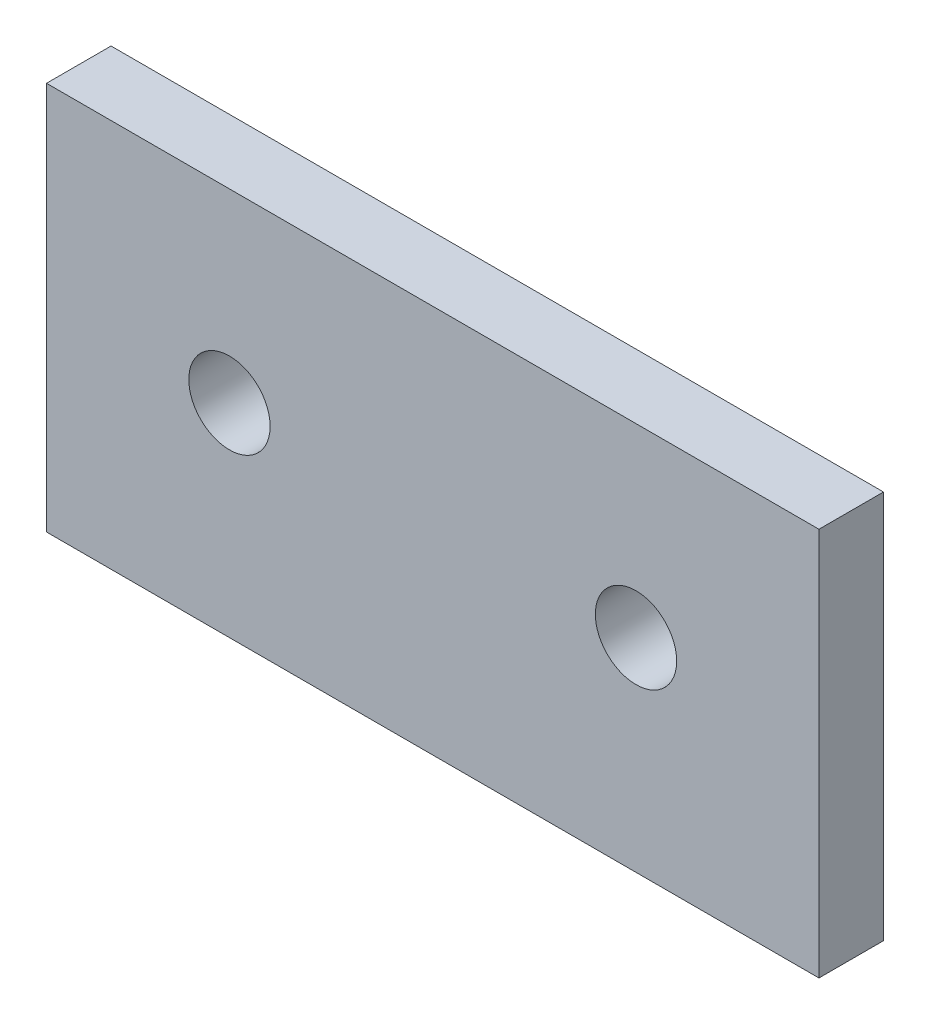
SolidWorks part; units mm, degrees
ref_plane "Front Plane" through (0, 0, 0) normal (0, 0, 1) x (1, 0, 0)
ref_plane "Top Plane" through (0, 0, 0) normal (0, 1, 0) x (1, 0, 0)
ref_plane "Right Plane" through (0, 0, 0) normal (1, 0, 0) x (0, 0, -1)
sketch "Sketch1" plane through (0, 0, 0) normal (0, 0, 1) x (1, 0, 0)
  line L1 (0, 42.5467) -> (76, 42.5467)
  line L2 (0, 42.5467) -> (0, 4.3086)
  line L3 (0, 4.3086) -> (76, 4.3086)
  line L4 (76, 42.5467) -> (76, 4.3086)
  circle A0 centre (18, 24.3086) radius 1.27
  circle A1 centre (58, 24.3086) radius 1.27
  dimension "D1" = 2.54
extrude "Boss-Extrude1" add sketch "Sketch1" along normal blind 6.35
hole_wizard "Ø8.0mm Dowel Hole1" positions "Sketch3" profile "Sketch2" hole size "Ø8.0" standard "ANSI Metric" end condition through all
sketch "Sketch3" plane through (0, 0, 6.35) normal (0, 0, 1) x (1, 0, 0)
  point P0 (18, 24.3086)
  point P3 (58, 24.3086)
sketch "Sketch2" plane through (18, 24.3086, 6.35) normal (1, 0, 0) x (0, -1, 0)
  line L0 (0, 0) -> (0, 6.35)
  line L1 (0, 6.35) -> (4, 6.35)
  line L2 (4, 6.35) -> (4, 0)
  line L5 (4, 0) -> (0, 0)
  line L11 (0, -6.35) -> (0, 107.95) construction
  dimension "Thru Hole Dia." = 8
  dimension "Thru Hole Depth" = 6.35
